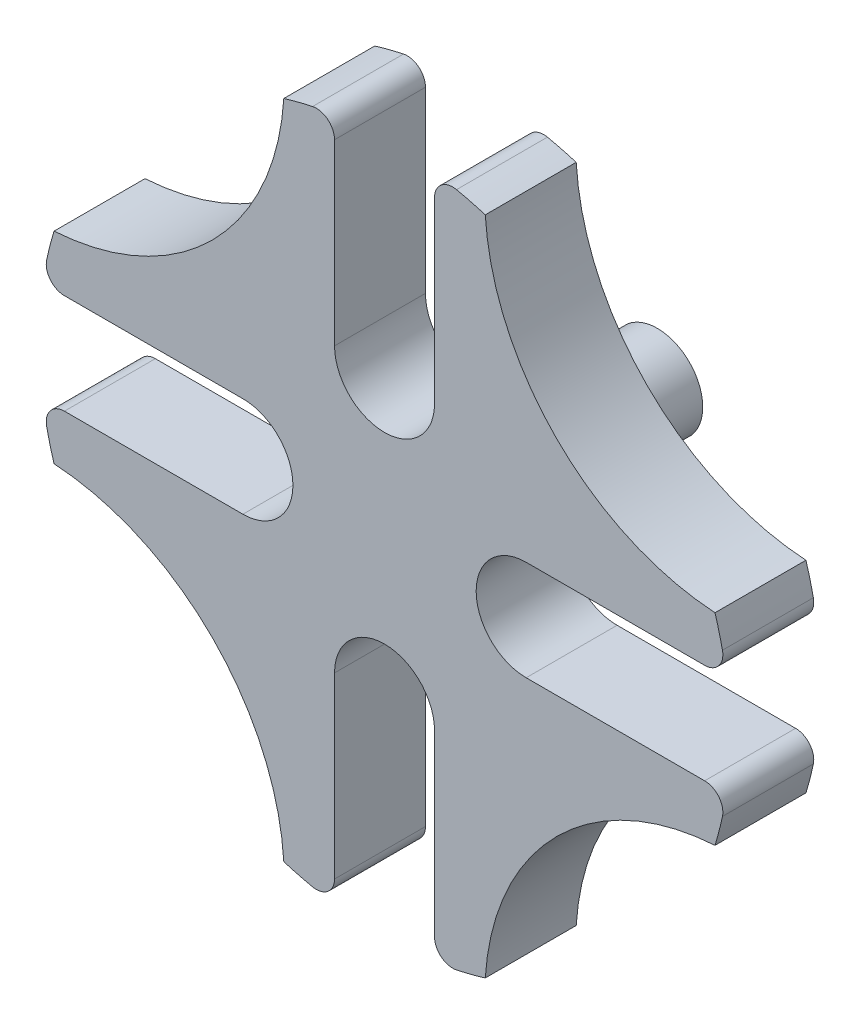
SolidWorks part; units mm, degrees
ref_plane "Alzado" through (0, 0, 0) normal (0, 0, 1) x (1, 0, 0)
ref_plane "Planta" through (0, 0, 0) normal (0, 1, 0) x (1, 0, 0)
ref_plane "Vista lateral" through (0, 0, 0) normal (1, 0, 0) x (0, 0, -1)
sketch "Croquis1" plane through (0, 0, 0) normal (0, 0, 1) x (1, 0, 0)
  line L0 (0, 85.6849) -> (0, 0) construction
  line L1 (0, 0) -> (-65.0725, 65.0725) construction
  line L2 (-5.5, 37.5999) -> (-5.5, 15.5778)
  line L3 (5.5, 15.5778) -> (5.5, 37.5999)
  line L4 (37.5999, 5.5) -> (15.5778, 5.5)
  line L5 (15.5778, -5.5) -> (37.5999, -5.5)
  line L6 (5.5, -37.5999) -> (5.5, -15.5778)
  line L7 (-5.5, -15.5778) -> (-5.5, -37.5999)
  line L8 (-37.5999, -5.5) -> (-15.5778, -5.5)
  line L9 (-15.5778, 5.5) -> (-37.5999, 5.5)
  arc A0 (-14.0398, -5.2806) -> (-5.2806, -14.0398) centre (0, 0) ccw
  arc A1 (-36.3486, 11.0805) -> (-37.5999, 5.5) centre (0, 0) ccw
  arc A4 (-5.5, 15.5778) -> (5.5, 15.5778) centre (0, 15.5778) ccw
  arc A5 (-5.5, 37.5999) -> (-11.0805, 36.3486) centre (0, 0) ccw
  arc A7 (15.5778, 5.5) -> (15.5778, -5.5) centre (15.5778, 0) ccw
  arc A9 (5.5, -15.5778) -> (-5.5, -15.5778) centre (0, -15.5778) ccw
  arc A11 (-15.5778, -5.5) -> (-15.5778, 5.5) centre (-15.5778, 0) ccw
  arc A12 (37.5999, 5.5) -> (36.3486, 11.0805) centre (0, 0) ccw
  arc A13 (36.3486, -11.0805) -> (37.5999, -5.5) centre (0, 0) ccw
  arc A14 (5.5, -37.5999) -> (11.0805, -36.3486) centre (0, 0) ccw
  arc A15 (-11.0805, -36.3486) -> (-5.5, -37.5999) centre (0, 0) ccw
  arc A16 (-37.5999, -5.5) -> (-36.3486, -11.0805) centre (0, 0) ccw
  arc A17 (11.0805, 36.3486) -> (5.5, 37.5999) centre (0, 0) ccw
  arc A18 (-5.2806, 14.0398) -> (-14.0398, 5.2806) centre (0, 0) ccw
  arc A19 (14.0398, 5.2806) -> (5.2806, 14.0398) centre (0, 0) ccw
  arc A20 (5.2806, -14.0398) -> (14.0398, -5.2806) centre (0, 0) ccw
  arc A22 (-36.3486, 11.0805) -> (-11.0805, 36.3486) centre (-38.0282, 38.0282) ccw
  arc A23 (11.0805, 36.3486) -> (36.3486, 11.0805) centre (38.0282, 38.0282) ccw
  arc A28 (36.3486, -11.0805) -> (11.0805, -36.3486) centre (38.0282, -38.0282) ccw
  arc A29 (-11.0805, -36.3486) -> (-36.3486, -11.0805) centre (-38.0282, -38.0282) ccw
  point P42 (0, 0)
  point P59 (0, 0)
  dimension "D1" = 30
  dimension "D2" = 76
  dimension "D5" = 4
  dimension "D8" = 27
  dimension "D4" = 45
  dimension "D6" = 11
  dimension "D7" = 4
extrude "Saliente-Extruir1" add sketch "Croquis1" along normal blind 10
sketch "Croquis2" plane through (0, 0, 0) normal (0, 0, -1) x (-1, 0, 0)
  circle A0 centre (0, 0) radius 5
  dimension "D1" = 10
extrude "Saliente-Extruir2" add sketch "Croquis2" along normal blind 20
fillet "Redondeo1" radius 2 8 edges at (-5.5, -37.5999, 5) (5.5, -37.5999, 5) (37.5999, -5.5, 5) (37.5999, 5.5, 5) (5.5, 37.5999, 5) (-5.5, 37.5999, 5) (-37.5999, 5.5, 5) (-37.5999, -5.5, 5)
